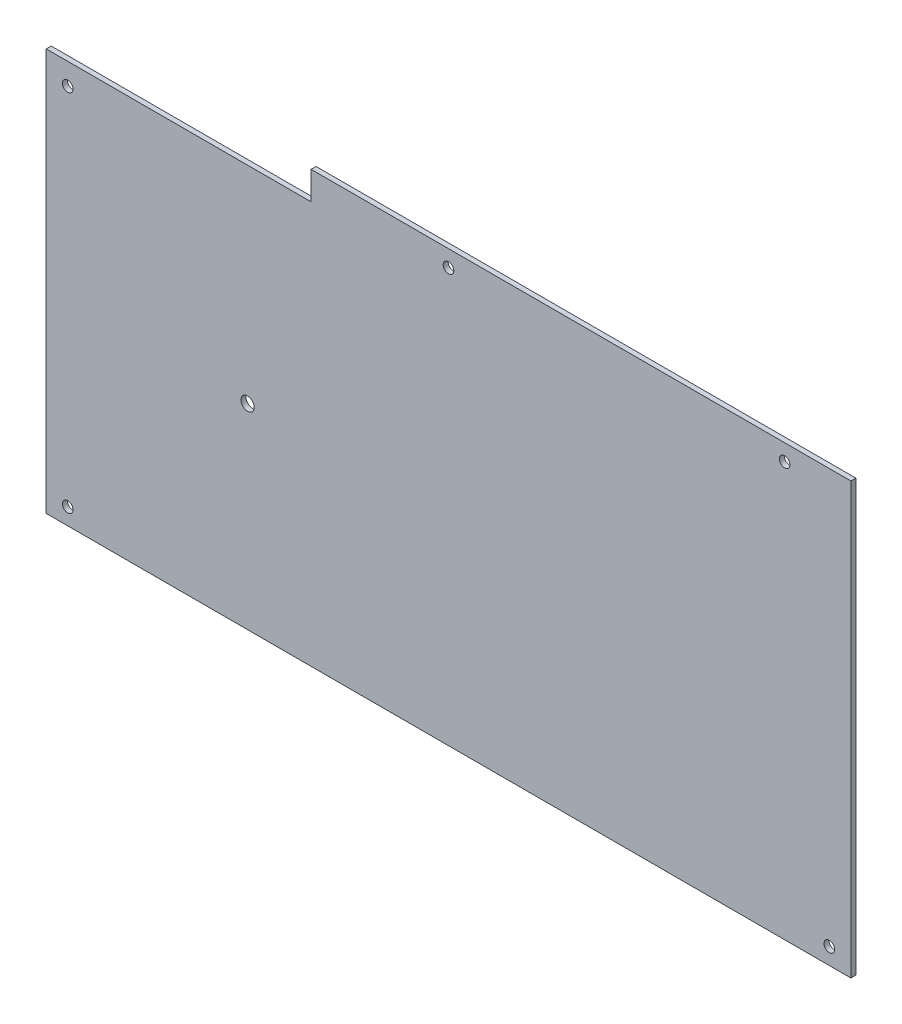
SolidWorks part; units mm, degrees
ref_plane "Front Plane" through (0, 0, 0) normal (0, 0, 1) x (1, 0, 0)
ref_plane "Top Plane" through (0, 0, 0) normal (0, 1, 0) x (1, 0, 0)
ref_plane "Right Plane" through (0, 0, 0) normal (1, 0, 0) x (0, 0, -1)
sketch "Sketch1" plane through (0, 0, 0) normal (0, 0, 1) x (1, 0, 0)
  line L0 (-241.5, -120) -> (1.5, -120)
  line L1 (1.5, -120) -> (1.5, 10)
  line L2 (1.5, 10) -> (-161.5, 10)
  line L3 (-161.5, 40) -> (-161.5, 1.5) construction
  line L4 (-161.5, 10) -> (-161.5, 1.5)
  line L5 (-161.5, 1.5) -> (-241.5, 1.5)
  line L6 (-241.5, -120) -> (-241.5, 21.5) construction
  line L7 (-241.5, 1.5) -> (-241.5, -120)
  circle A0 centre (-180.67, -60.8705) radius 2
  dimension "D1" = 4
extrude "Boss-Extrude1" add sketch "Sketch1" along normal blind 1.5
sketch "Sketch2" plane through (0, 0, 1.5) normal (0, 0, 1) x (1, 0, 0)
  line L0 (-120, -120) -> (-120, 17.2737) construction
  line L1 (-241.5, -120) -> (1.5, -120) construction
  line L2 (1.5, 10) -> (-161.5, 10) construction
  line L3 (1.5, -120) -> (1.5, 10) construction
  circle A0 centre (-235, -5) radius 1.6
  circle A1 centre (-235, -115) radius 1.6
  circle A2 centre (-5, -115) radius 1.6
  circle A3 centre (-120, 5) radius 1.6
  circle A4 centre (-18.5, 5) radius 1.6
  dimension "D1" = 3.2
  dimension "D2" = 3.2
  dimension "D3" = 3.2
  dimension "D4" = 3.2
  dimension "D7" = 3.2
  dimension "D5" = 5
  dimension "D6" = 20
  dimension "D8" = 5
extrude "Cut-Extrude1" cut sketch "Sketch2" against normal blind 1.5
